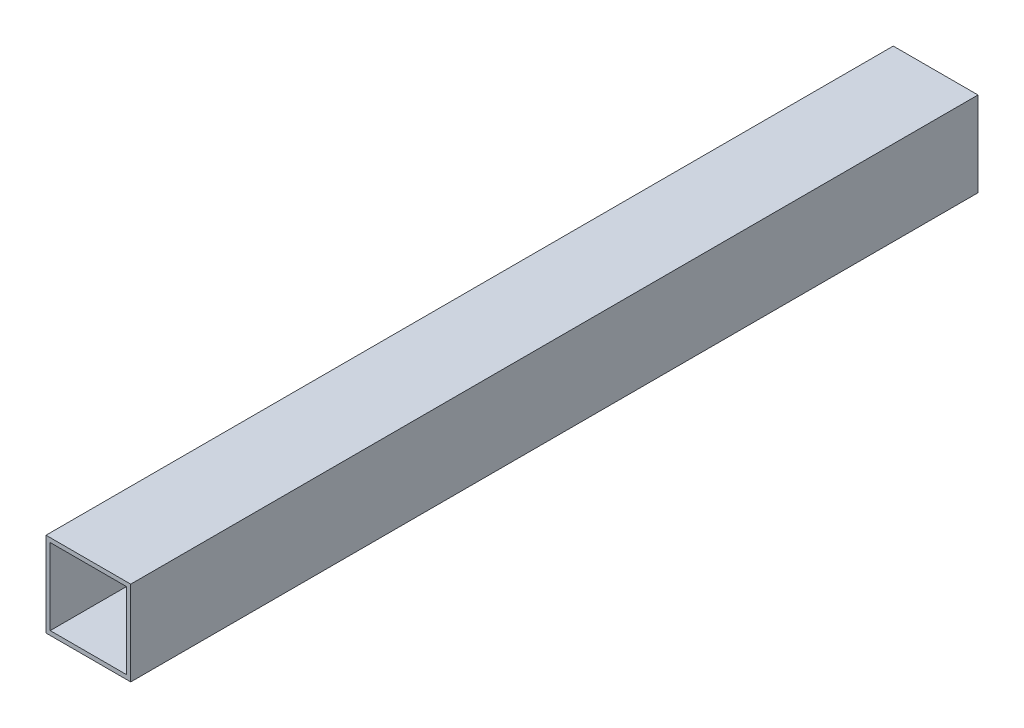
SolidWorks part; units mm, degrees
ref_plane "Plan de face" through (0, 0, 0) normal (0, 0, 1) x (1, 0, 0)
ref_plane "Plan de dessus" through (0, 0, 0) normal (0, 1, 0) x (1, 0, 0)
ref_plane "Plan de droite" through (0, 0, 0) normal (1, 0, 0) x (0, 0, -1)
sketch "Esquisse1" plane through (0, 0, 0) normal (0, 0, 1) x (1, 0, 0)
  line L0 (-450, 450) -> (450, 450)
  line L1 (-500, -500) -> (500, -500)
  line L2 (-500, -500) -> (-500, 500)
  line L3 (-500, 500) -> (500, 500)
  line L4 (500, -500) -> (500, 500)
  line L5 (-500, -500) -> (500, 500) construction
  line L6 (-500, 500) -> (500, -500) construction
  line L7 (450, -450) -> (450, 450)
  line L8 (-450, -450) -> (450, -450)
  line L9 (-450, -450) -> (-450, 450)
  point P0 (0, 0)
  dimension "D1" = 1000
  dimension "D2" = 1000
  dimension "D3" = 50
extrude "Boss.-Extru.1" add sketch "Esquisse1" along normal blind 10000
